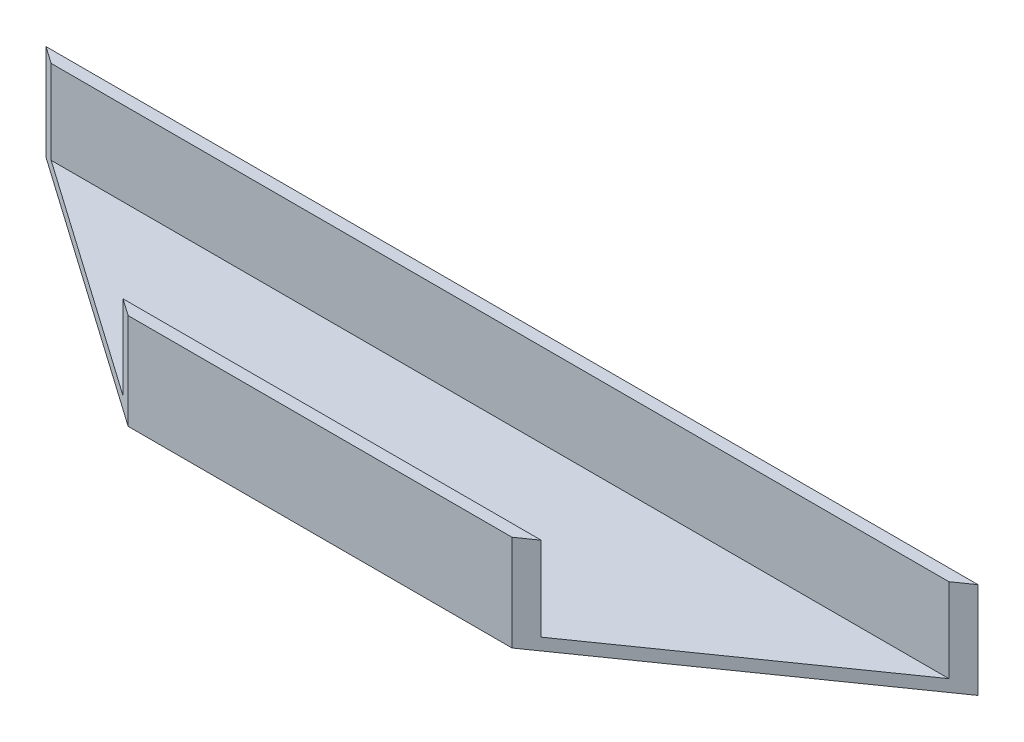
SolidWorks part; units mm, degrees
ref_plane "Front Plane" through (0, 0, 0) normal (0, 0, 1) x (1, 0, 0)
ref_plane "Top Plane" through (0, 0, 0) normal (0, 1, 0) x (1, 0, 0)
ref_plane "Right Plane" through (0, 0, 0) normal (1, 0, 0) x (0, 0, -1)
sketch "Sketch1" plane through (0, 0, 0) normal (1, 0, 0) x (0, 0, -1)
  line L0 (-22.225, -9.525) -> (-22.225, 12.7)
  line L1 (-25.4, -12.7) -> (25.4, -12.7)
  line L2 (-25.4, -12.7) -> (-25.4, 12.7)
  line L3 (-22.225, -9.525) -> (22.225, -9.525)
  line L4 (25.4, -12.7) -> (25.4, 12.7)
  line L5 (22.225, -9.525) -> (22.225, 12.7)
  line L6 (-25.4, 12.7) -> (-22.225, 12.7)
  line L7 (25.4, 12.7) -> (22.225, 12.7)
  dimension "D1" = 25.4
  dimension "D2" = 50.8
  dimension "D3" = 3.175
extrude "Boss-Extrude1" add sketch "Sketch1" along normal blind 406.4
sketch "Sketch2" plane through (0, 12.7, 0) normal (0, 1, 0) x (1, 0, 0)
  line L0 (203.2, -25.4) -> (203.2, 25.4) construction
  line L1 (406.4, -25.4) -> (0, -25.4) construction
  line L2 (406.4, 25.4) -> (0, 25.4) construction
  line L3 (203.2, -25.4) -> (152.4, -25.4)
  line L4 (152.4, -25.4) -> (79.8501, 25.4)
  line L5 (203.2, -25.4) -> (254, -25.4)
  line L6 (254, -25.4) -> (326.5499, 25.4)
  line L7 (79.8501, 25.4) -> (-62.2103, 25.4)
  line L8 (-62.2103, 25.4) -> (-62.2103, -94.2741)
  line L9 (326.5499, 25.4) -> (523.3731, 25.4)
  line L10 (523.3731, 25.4) -> (523.3731, -141.4536)
  line L11 (523.3731, -141.4536) -> (-62.2103, -94.2741)
  dimension "D1" = 50.8
  dimension "D2" = 35
extrude "Cut-Extrude1" cut sketch "Sketch2" against normal through all
